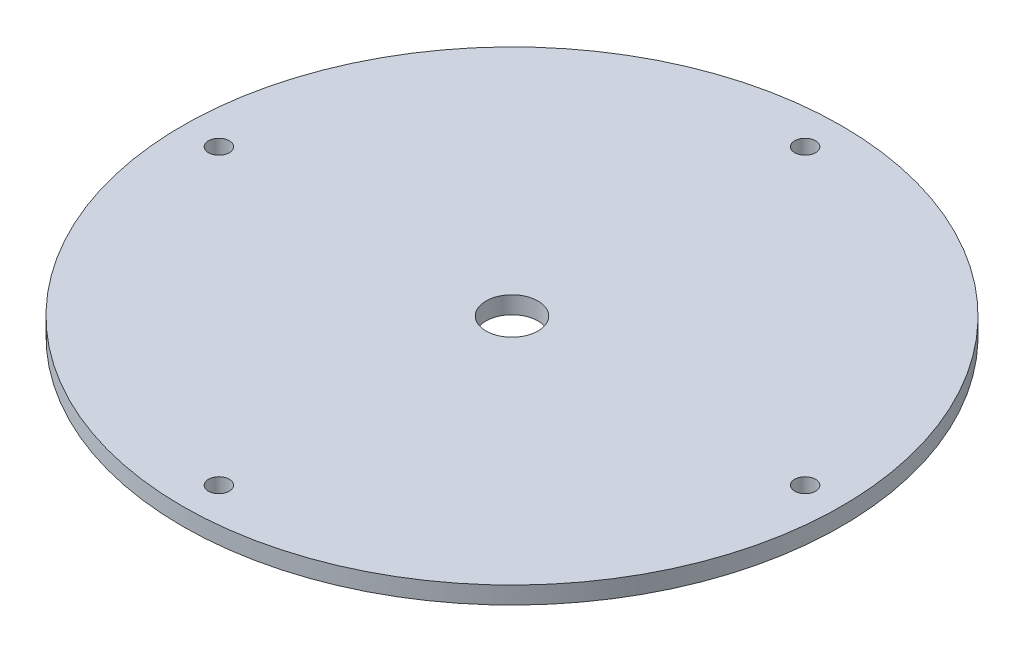
SolidWorks part; units mm, degrees
ref_plane "Front Plane" through (0, 0, 0) normal (0, 0, 1) x (1, 0, 0)
ref_plane "Top Plane" through (0, 0, 0) normal (0, 1, 0) x (1, 0, 0)
ref_plane "Right Plane" through (0, 0, 0) normal (1, 0, 0) x (0, 0, -1)
sketch "Sketch2" plane through (0, 0, 0) normal (0, 1, 0) x (1, 0, 0)
  line L0 (0, 80.5682) -> (0, -100.1481) construction
  line L1 (0, 0) -> (0, 84.5) construction
  circle A0 centre (0, 0) radius 95
  circle A1 centre (0, 0) radius 7.5
  circle A2 centre (0, 84.5) radius 3
  circle A3 centre (84.5, 0) radius 3
  circle A4 centre (0, -84.5) radius 3
  circle A5 centre (-84.5, 0) radius 3
  dimension "OuterDiameter" = 190
  dimension "InternalDiameter" = 15
  dimension "MountingBoltDiameter" = 6
  dimension "D2" = 84.5
  dimension "D3" = 0
  dimension "D1" = 4
extrude "Boss-Extrude1" add sketch "Sketch2" along normal blind 5
equation "\"ExternalDiameter\"= 190mm"
equation "\"ConnectorExternalDiameter\"= 180mm"
equation "\"ConnectorInternalDiameter\"= 158"
equation "\"InternalDiameter\"= 15"
equation "\"OuterDiameter@Sketch2\"= \"ExternalDiameter\""
equation "\"InternalDiameter@Sketch2\"= \"InternalDiameter\""
equation "\"MountingBoltDiameter\"= 6"
equation "\"MountingBoltDiameter@Sketch2\"= \"MountingBoltDiameter\""
equation "\"D2@Sketch2\"= 0.25 * ( \"ConnectorExternalDiameter\" + \"ConnectorInternalDiameter\" )"
